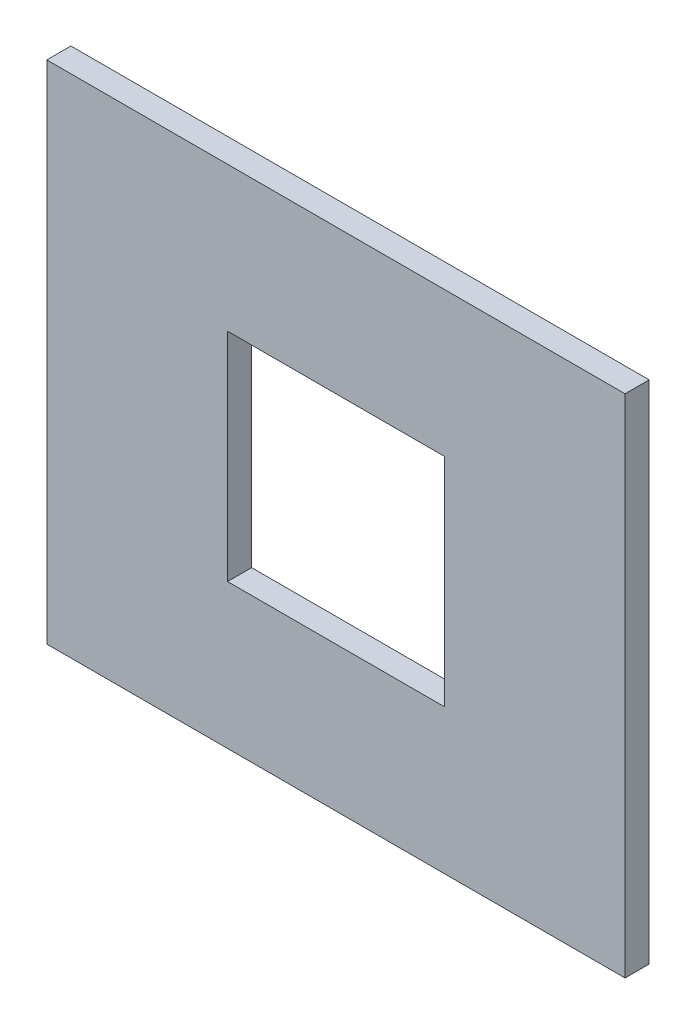
SolidWorks part; units mm, degrees
ref_plane "Front" through (0, 0, 0) normal (0, 0, 1) x (1, 0, 0)
ref_plane "Top" through (0, 0, 0) normal (0, 1, 0) x (1, 0, 0)
ref_plane "Right" through (0, 0, 0) normal (1, 0, 0) x (0, 0, -1)
sketch "Sketch1" plane through (0, 0, 0) normal (0, 0, 1) x (1, 0, 0)
  line L0 (0, 133.35) -> (0, -133.35) construction
  line L1 (-152.4, 133.35) -> (152.4, 133.35)
  line L2 (-152.4, 133.35) -> (-152.4, -133.35)
  line L3 (-152.4, -133.35) -> (152.4, -133.35)
  line L4 (152.4, 133.35) -> (152.4, -133.35)
  line L5 (-152.4, 0) -> (152.4, 0) construction
  line L6 (-57.15, 57.15) -> (57.15, 57.15)
  line L7 (-57.15, 57.15) -> (-57.15, -57.15)
  line L8 (-57.15, -57.15) -> (57.15, -57.15)
  line L9 (57.15, 57.15) -> (57.15, -57.15)
  point P10 (0, 57.15)
  point P14 (-57.15, 0)
  dimension "D2" = 114.3
  dimension "D1" = 266.7
  dimension "D3" = 304.8
extrude "Extrude1" add sketch "Sketch1" along normal blind 12.7
